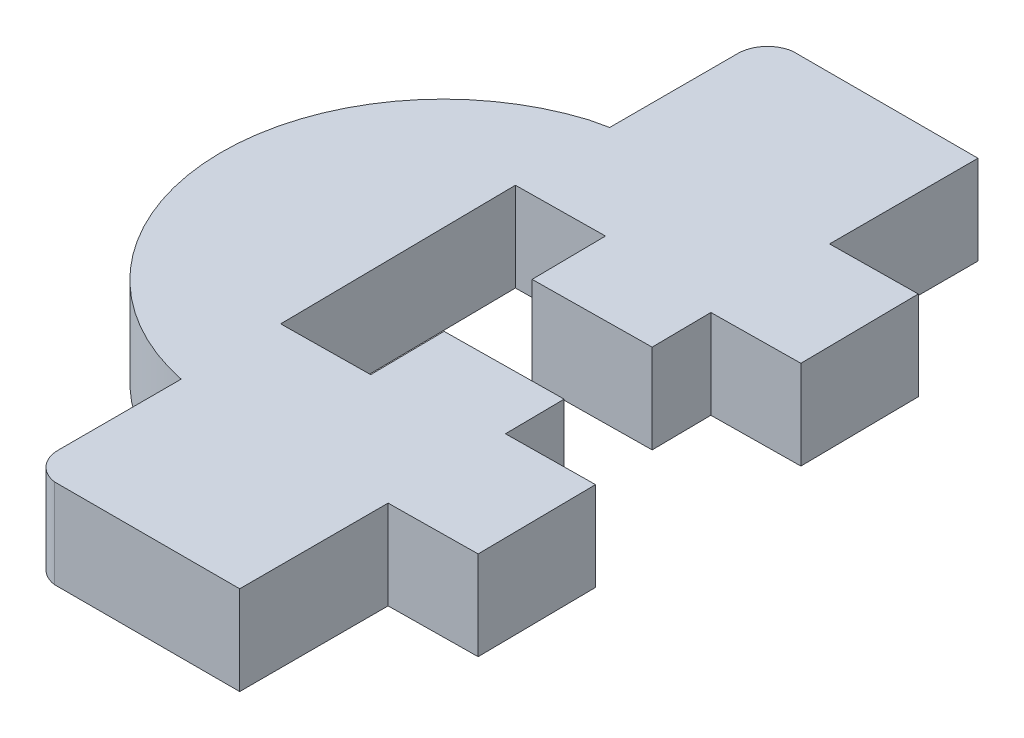
SolidWorks part; units mm, degrees
material "Balsa"
ref_plane "Alzado" through (0, 0, 0) normal (0, 0, 1) x (1, 0, 0)
ref_plane "Planta" through (0, 0, 0) normal (0, 1, 0) x (1, 0, 0)
ref_plane "Vista lateral" through (0, 0, 0) normal (1, 0, 0) x (0, 0, -1)
sketch "Croquis1" plane through (0, 0, 0) normal (0, 1, 0) x (1, 0, 0)
  line L0 (33638.8996, 12674.8023) -> (33638.3132, 12674.6695)
  line L1 (33646.0591, 12666.1104) -> (33646.0819, 12664.1106)
  line L2 (33642.0594, 12666.065) -> (33646.0591, 12666.1104)
  line L3 (33642.0878, 12663.5652) -> (33642.0594, 12666.065)
  line L4 (33639.088, 12663.5311) -> (33642.0878, 12663.5652)
  line L5 (33639.0596, 12666.0309) -> (33639.088, 12663.5311)
  line L6 (33638.9971, 12671.5305) -> (33639.0255, 12669.0307)
  line L7 (33641.9969, 12671.5646) -> (33638.9971, 12671.5305)
  line L8 (33642.0253, 12669.0648) -> (33641.9969, 12671.5646)
  line L9 (33646.0251, 12669.1102) -> (33642.0253, 12669.0648)
  line L10 (33646.0023, 12671.1101) -> (33646.0251, 12669.1102)
  line L11 (33649.0021, 12671.1442) -> (33646.0023, 12671.1101)
  line L12 (33646.0819, 12664.1106) -> (33649.0817, 12664.1447)
  line L13 (33648.9567, 12675.1439) -> (33646.0023, 12675.1104)
  line L14 (33649.1271, 12660.1449) -> (33649.0817, 12664.1447)
  line L15 (33646.1271, 12660.1108) -> (33649.1271, 12660.1449)
  line L16 (33649.0021, 12671.1442) -> (33648.9567, 12675.1439)
  line L17 (33639.0596, 12666.0309) -> (33639.0255, 12669.0307)
  line L18 (33646.0023, 12675.1104) -> (33646.0023, 12680.1104)
  line L19 (33646.0023, 12680.1104) -> (33639.759, 12680.1104)
  line L20 (33638.8996, 12679.1216) -> (33638.8996, 12674.8023)
  line L21 (33646.1273, 12660.1108) -> (33646.1273, 12655.1108)
  line L22 (33646.1273, 12655.1108) -> (33639.884, 12655.1108)
  line L23 (33639.0246, 12656.0997) -> (33639.0246, 12660.2414)
  arc A0 (33638.3132, 12674.6695) -> (33639.0246, 12660.2414) centre (33640.5425, 12667.5479) ccw
  arc A1 (33639.759, 12680.1104) -> (33638.8996, 12679.1216) centre (33639.8982, 12679.1216) ccw
  arc A2 (33639.0246, 12656.0997) -> (33639.884, 12655.1108) centre (33640.0232, 12656.0997) ccw
  dimension "D1" = 15
extrude "Saliente-Extruir1" add sketch "Croquis1" along normal blind 3
